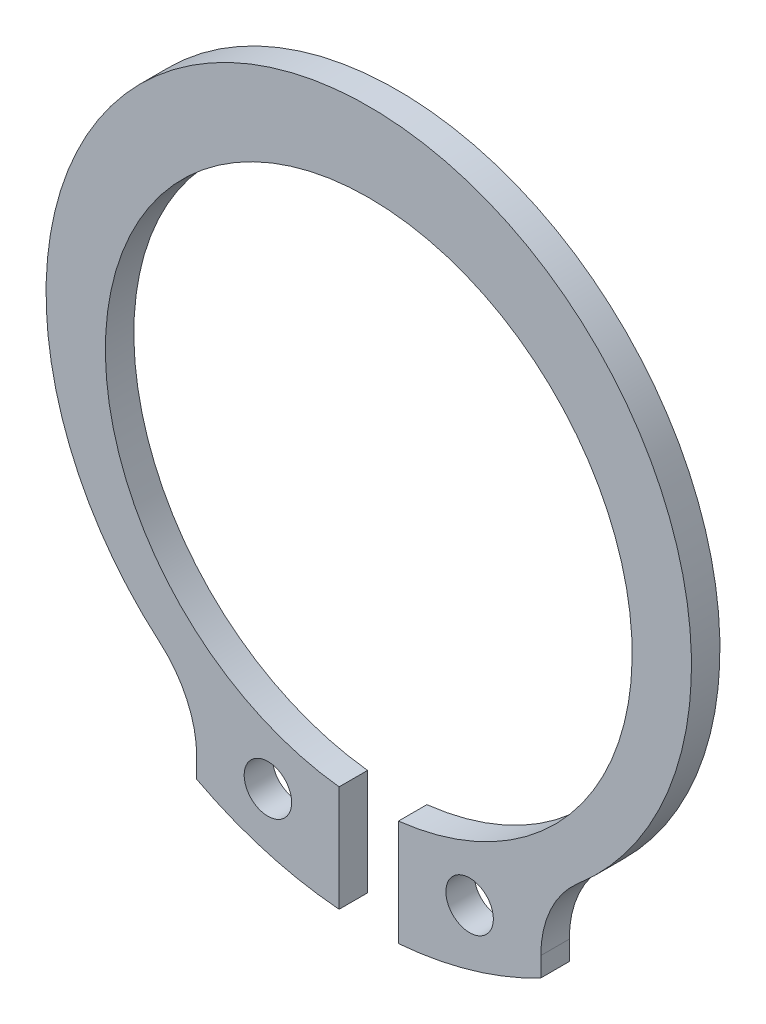
SolidWorks part; units mm, degrees
ref_plane "Front" through (0, 0, 0) normal (0, 0, 1) x (1, 0, 0)
ref_plane "Top" through (0, 0, 0) normal (0, 1, 0) x (1, 0, 0)
ref_plane "Right" through (0, 0, 0) normal (1, 0, 0) x (0, 0, -1)
sketch "Sketch1" plane through (0, 0, 0) normal (0, 0, 1) x (1, 0, 0)
  line L0 (0, 4.2365) -> (0, -4.2365) construction
  line L1 (-1.25, -16.3297) -> (-1.25, -11.8594)
  line L2 (1.25, -16.3297) -> (1.25, -11.8594)
  line L3 (-4.25, -5.6295) -> (-4.25, -13.4327) construction
  line L4 (-7.25, -11.5064) -> (-7.25, -14.5865)
  line L5 (7.25, -11.5064) -> (7.25, -14.5865)
  line L6 (4.25, -5.6295) -> (4.25, -13.4327) construction
  line L7 (13.3, -0.83) -> (-13.3, -0.83) construction
  line L8 (0, -0.83) -> (-1.7511, -16.2811) construction
  arc A0 (1.25, -11.8594) -> (-1.25, -11.8594) centre (0, -0.83) ccw
  arc A1 (7.25, -11.5064) -> (-7.25, -11.5064) centre (0, 0) ccw
  arc A2 (-13.3, -0.83) -> (13.3, -0.83) centre (0, -0.83) ccw construction
  circle A3 centre (-4.25, -13.4327) radius 1
  arc A4 (-7.25, -14.5865) -> (-1.25, -16.3297) centre (0, -0.83) ccw
  circle A5 centre (4.25, -13.4327) radius 1
  arc A6 (7.25, -14.5865) -> (1.25, -16.3297) centre (0, -0.83) cw
  dimension "d0" = 22.2
  dimension "D" = 27.2
  dimension "d1" = 2
  dimension "R1" = 13.3
  dimension "B1" = 2.5
  dimension "c" = 0.83
  dimension "L" = 14.5
  dimension "B2" = 8.5
  dimension "a" = 4.45
extrude "Body" add sketch "Sketch1" against normal blind 1.2
fillet "Fillet1" radius 4.5 2 edges at (-7.25, -11.5064, -0.6) (7.25, -11.5064, -0.6)
